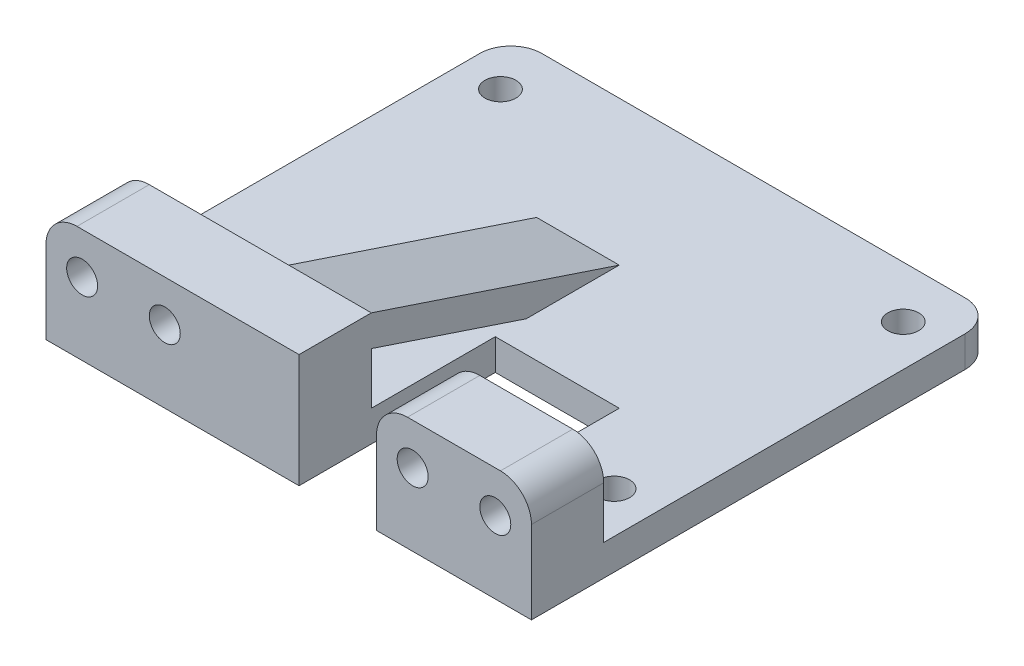
SolidWorks part; units mm, degrees
material "聚脂树脂"
ref_plane "前视基准面" through (0, 0, 0) normal (0, 0, 1) x (1, 0, 0)
ref_plane "上视基准面" through (0, 0, 0) normal (0, 1, 0) x (1, 0, 0)
ref_plane "右视基准面" through (0, 0, 0) normal (1, 0, 0) x (0, 0, -1)
other "Configuration Table"
sketch "草图1" plane through (0, 0, 0) normal (0, 1, 0) x (1, 0, 0)
  line L0 (0, 0) -> (28.4871, 0) construction
  line L1 (-23.5, -19) -> (23.5, -19)
  line L2 (-23.5, -19) -> (-23.5, 19)
  line L3 (-23.5, 19) -> (23.5, 19)
  line L4 (23.5, -19) -> (23.5, 19)
  line L5 (-23.5, -19) -> (23.5, 19) construction
  line L6 (-23.5, 19) -> (23.5, -19) construction
  line L7 (0, 0) -> (0, 25.7908) construction
  line L8 (1, -19) -> (1, -7)
  line L9 (1, -7) -> (13, -7)
  line L10 (13, -7) -> (13, -19)
  circle A0 centre (19.5, 14) radius 1.5
  circle A1 centre (19.5, -14) radius 1.5
  circle A2 centre (-19.5, -14) radius 1.5
  circle A3 centre (-19.5, 14) radius 1.5
  point P0 (0, 0)
  dimension "D1" = 3
  dimension "D2" = 39
  dimension "D3" = 28
  dimension "D4" = 47
  dimension "D5" = 38
  dimension "D6" = 12
  dimension "D7" = 12
  dimension "D8" = 1
extrude "凸台-拉伸1" add sketch "草图1" along normal blind 3 contours L9 L10 L1 L4 L3 L2 L8 A1 A0 A2 A3
sketch "草图2" plane through (0, 0, 19) normal (0, 0, 1) x (1, 0, 0)
  line L0 (0, 0) -> (0, 15.913) construction
  line L1 (-23.5, 0) -> (-23.5, 11)
  line L2 (-23.5, 11) -> (0, 11)
  line L3 (0, 11) -> (0, 0)
  line L4 (-23.5, 0) -> (1, 0) construction
  line L5 (0, 0) -> (-23.5, 0)
  line L8 (23.5, 11) -> (23.5, 0)
  line L10 (23.5, 0) -> (8.5, 0)
  line L11 (8.5, 0) -> (8.5, 11)
  line L12 (8.5, 11) -> (23.5, 11)
  line L13 (0, 0) -> (1, 0)
  line L14 (1, 0) -> (1, 11)
  line L15 (1, 11) -> (0, 11)
  circle A0 centre (12, 7) radius 1.5
  circle A1 centre (20, 7) radius 1.5
  circle A2 centre (-20, 7) radius 1.5
  circle A3 centre (-12, 7) radius 1.5
  line M10 (-23.5, 0) -> (1, 0)
  line M11 (1, 0) -> (1, 3)
  line M12 (1, 3) -> (-23.5, 3)
  line M13 (-23.5, 3) -> (-23.5, 0)
  dimension "D4" = 3
  dimension "D5" = 3
  dimension "D6" = 8
  dimension "D9" = 7
  dimension "D10" = 7
  dimension "16.5" = 23.5
  dimension "D2" = 11
  dimension "D3" = 11
  dimension "D7" = 15
  dimension "D8" = 3.5
  dimension "D11" = 0
extrude "凸台-拉伸2" add sketch "草图2" along normal blind 7 contours L14 L15 L3 M12 | L3 L2 L1 M12 | L3 M12 M13 M10 | L3 M12 M10 M11 | L12 L11 L10 L8 A1 A0
fillet "圆角2" radius 3 2 edges at (23.5, 1.5, -19) (-23.5, 1.5, -19)
sketch "草图3" plane through (1, 0, 0) normal (1, 0, 0) x (0, 0, -1)
  line L0 (-19, 11) -> (-19, 8)
  line L1 (-19, 11) -> (5, 3)
  line L2 (-19, 3) -> (16, 3) construction
  line L3 (5, 3) -> (-4, 3)
  line L4 (-4, 3) -> (-19, 8)
  dimension "D1" = 3
  dimension "D2" = 9
extrude "凸台-拉伸3" add sketch "草图3" against normal blind 8
fillet "圆角3" radius 3 1 edges at (13, 1.5, 19)
fillet "圆角4" radius 3 3 edges at (-23.5, 11, 22.5) (8.5, 11, 22.5) (23.5, 11, 22.5)
